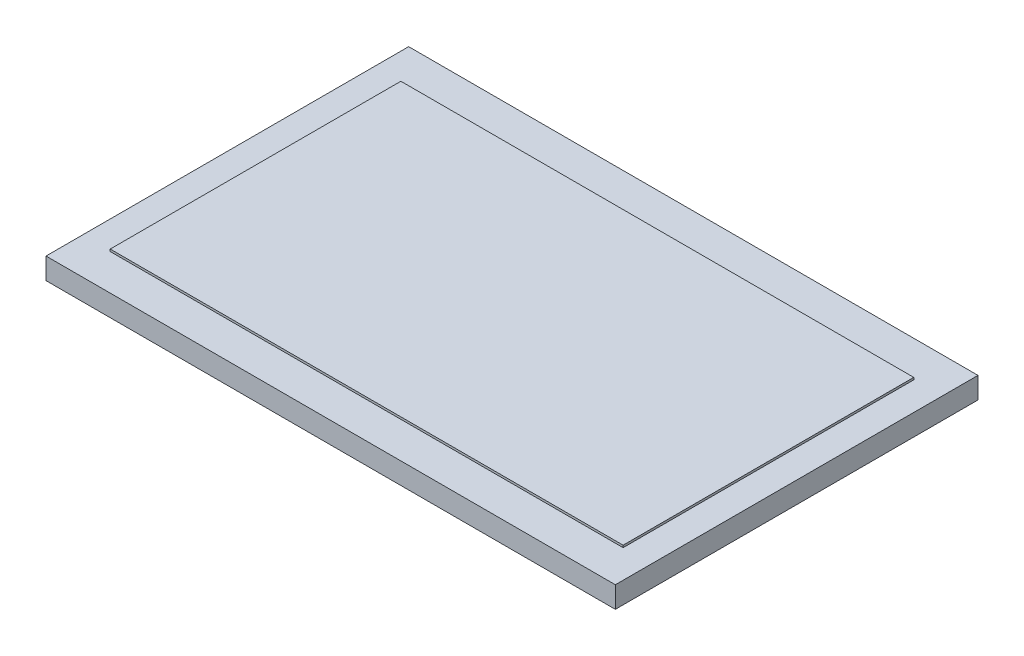
SolidWorks part; units mm, degrees
ref_plane "Front" through (0, 0, 0) normal (0, 0, 1) x (1, 0, 0)
ref_plane "Top" through (0, 0, 0) normal (0, 1, 0) x (1, 0, 0)
ref_plane "Right" through (0, 0, 0) normal (1, 0, 0) x (0, 0, -1)
sketch "Sketch1" plane through (0, 0, 0) normal (0, 1, 0) x (1, 0, 0)
  line L1 (0, 0) -> (105.5, 0)
  line L2 (0, 0) -> (0, 67.2)
  line L3 (0, 67.2) -> (105.5, 67.2)
  line L4 (105.5, 0) -> (105.5, 67.2)
  dimension "D1" = 105.5
  dimension "D2" = 67.2
extrude "Boss-Extrude1" add sketch "Sketch1" along normal blind 3.95
sketch "Sketch2" plane through (0, 3.95, 0) normal (0, 1, 0) x (1, 0, 0)
  line L0 (0, 67.2) -> (0, 0) construction
  line L1 (5.23, 60.526) -> (100.27, 60.526)
  line L2 (5.23, 60.526) -> (5.23, 6.67)
  line L3 (5.23, 6.67) -> (100.27, 6.67)
  line L4 (100.27, 60.526) -> (100.27, 6.67)
  line L5 (0, 0) -> (105.5, 0) construction
  dimension "D1" = 95.04
  dimension "D2" = 53.856
  dimension "D3" = 5.23
  dimension "D4" = 6.67
extrude "Boss-Extrude2" add sketch "Sketch2" along normal blind 0.4
